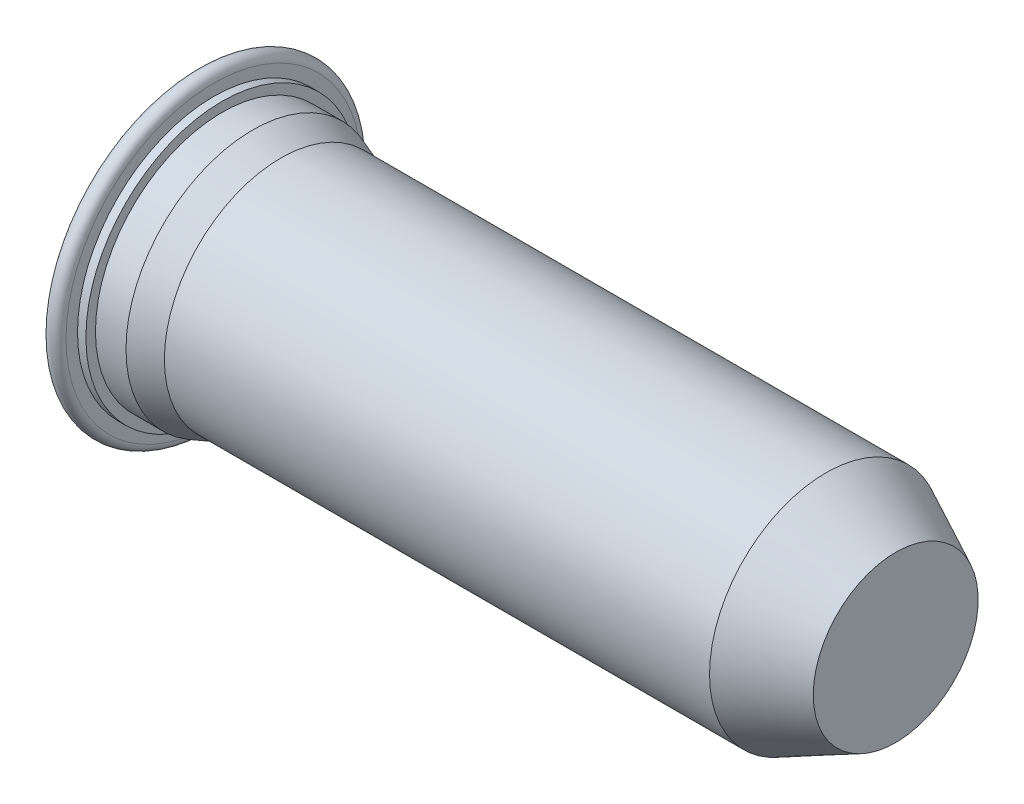
SolidWorks part; units mm, degrees
ref_plane "Plane1" through (0, 0, 0) normal (0, 0, 1) x (1, 0, 0)
ref_plane "Plane2" through (0, 0, 0) normal (0, 1, 0) x (1, 0, 0)
ref_plane "Plane3" through (0, 0, 0) normal (1, 0, 0) x (0, 0, -1)
sketch "BodySke" plane through (0, 0, 0) normal (0, 0, 1) x (1, 0, 0)
  line L0 (0, 0) -> (0, 4.0234)
  line L1 (0.4572, 4.0284) -> (0.4572, 3.7147)
  line L2 (19.05, 2.2479) -> (17.1492, 3.175)
  line L3 (2.286, 3.175) -> (17.1492, 3.175)
  line L4 (19.05, 2.2479) -> (19.05, 0)
  line L5 (19.05, 0) -> (0, 0)
  line L6 (0, 0) -> (50.554, 0) construction
  line L7 (0.4572, 3.7147) -> (0.6858, 3.7147)
  line L8 (1.5184, 3.4544) -> (0.6858, 3.4544)
  line L9 (-9.525, 4.2545) -> (9.525, 4.2545) construction
  line L10 (0.6858, 3.7147) -> (0.6858, 3.4544)
  line L11 (2.286, 3.175) -> (1.5184, 3.4544)
  line L13 (9.525, -4.2545) -> (-9.525, -4.2545) construction
  line L14 (0.0051, 4.0284) -> (0.0051, 4.0234)
  line L15 (0, 4.0234) -> (0.0051, 4.0234)
  arc A0 (0.0051, 4.0284) -> (0.4572, 4.0284) centre (0.2311, 4.0284) cw
  dimension "Length" = 19.05
  dimension "H_dia" = 8.509
  dimension "D1" = 0.0051
  dimension "D2" = 0.0051
  dimension "T_dim" = 0.4572
  dimension "Diameter" = 6.35
  dimension "Neck_dia" = 6.9088
  dimension "Neck_len" = 2.286
  dimension "D3" = 20
  dimension "D4" = 64
  dimension "D_dia" = 4.4958
  dimension "Clinch_dia" = 7.4295
  dimension "Clinch_ht" = 0.6858
revolve "BaseBody" add sketch "BodySke" angle 360 about L6
cosmetic thread "ThreadCosmetic" [suppressed] parameters "Thread_length"=15.621, "Thread_minor"=4.8387
equation "' \"Diameter@BodySke\" = 0.25"
equation "' \"Length@BodySke\" = 0.75"
equation "' \"Neck_dia@BodySke\" = 0.272"
equation "' \"H_dia@BodySke\" = 0.335"
equation "' \"Neck_len@BodySke\" = 0.09"
equation "' \"D_dia@BodySke\" = 0.177"
equation "\"T_dim@BodySke\" = \"Neck_len@BodySke\" * 0.2"
equation "\"Clinch_dia@BodySke\" = ( \"H_dia@BodySke\" + \"Diameter@BodySke\" ) / 2"
equation "\"Clinch_ht@BodySke\" = \"T_dim@BodySke\" * 1.5"
